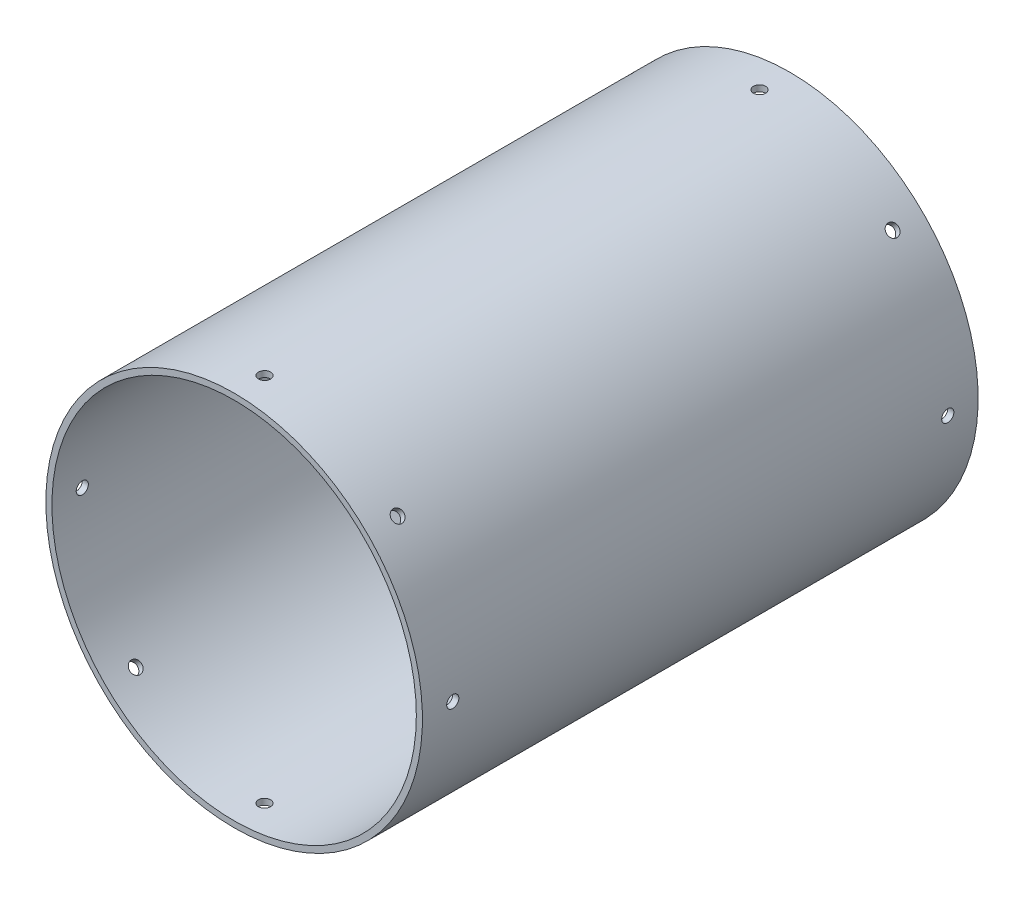
SolidWorks part; units mm, degrees
ref_plane "Front Plane" through (0, 0, 0) normal (1, 0, 0) x (0, 1, 0)
ref_plane "Top Plane" through (0, 0, 0) normal (0, 0, 1) x (0, 1, 0)
ref_plane "Right Plane" through (0, 0, 0) normal (0, 1, 0) x (-1, 0, 0)
sketch "Sketch1" plane through (0, 0, 0) normal (0, 0, 1) x (0, 1, 0)
  circle A1 centre (0, 0) radius 30
  dimension "D1" = 60
extrude "Extrude-Thin1" add sketch "Sketch1" along normal blind 91.5 thin
sketch "Sketch4" plane through (0, 0, 0) normal (1, 0, 0) x (0, 1, 0)
  line L1 (30, 91.5) -> (-30, 91.5) construction
  circle A0 centre (0, 5) radius 1
  circle A1 centre (0, 86.5) radius 1
  dimension "D2" = 2
  dimension "D1" = 5
  dimension "D3" = 5
extrude "Cut-Extrude1" cut sketch "Sketch4" against normal through all both and the other way through all
pattern_circular "CirPattern1" count 4 every 45 about axis through (0, 0, 91.5) along (0, 0, -1) of "Cut-Extrude1"
sketch "Sketch6" plane through (0, 0, 0) normal (1, 0, 0) x (0, 1, 0)
  line L0 (-3.5, 36.25) -> (3.5, 36.25) construction
  line L1 (-3.5, 39.25) -> (3.5, 39.25)
  line L2 (-3.5, 33.25) -> (3.5, 33.25)
  arc A0 (-3.5, 39.25) -> (-3.5, 33.25) centre (-3.5, 36.25) ccw
  arc A1 (3.5, 33.25) -> (3.5, 39.25) centre (3.5, 36.25) ccw
  point P2 (0, 36.25)
  dimension "D2" = 3
  dimension "D1" = 7
  dimension "D3" = 36.25
extrude "Cut-Extrude3" cut sketch "Sketch6" against normal through all
sketch "Sketch7" plane through (0, 0, 0) normal (0, 1, 0) x (-1, 0, 0)
  line L0 (-15, 42.5) -> (0, 42.5) construction
  line L1 (-15, 47.5) -> (0, 47.5)
  line L2 (-15, 37.5) -> (0, 37.5)
  arc A0 (-15, 47.5) -> (-15, 37.5) centre (-15, 42.5) ccw
  arc A1 (0, 37.5) -> (0, 47.5) centre (0, 42.5) ccw
  point P2 (-7.5, 42.5)
  dimension "D1" = 10
  dimension "D2" = 15
  dimension "D3" = 42.5
extrude "Cut-Extrude4" cut sketch "Sketch7" against normal through all
